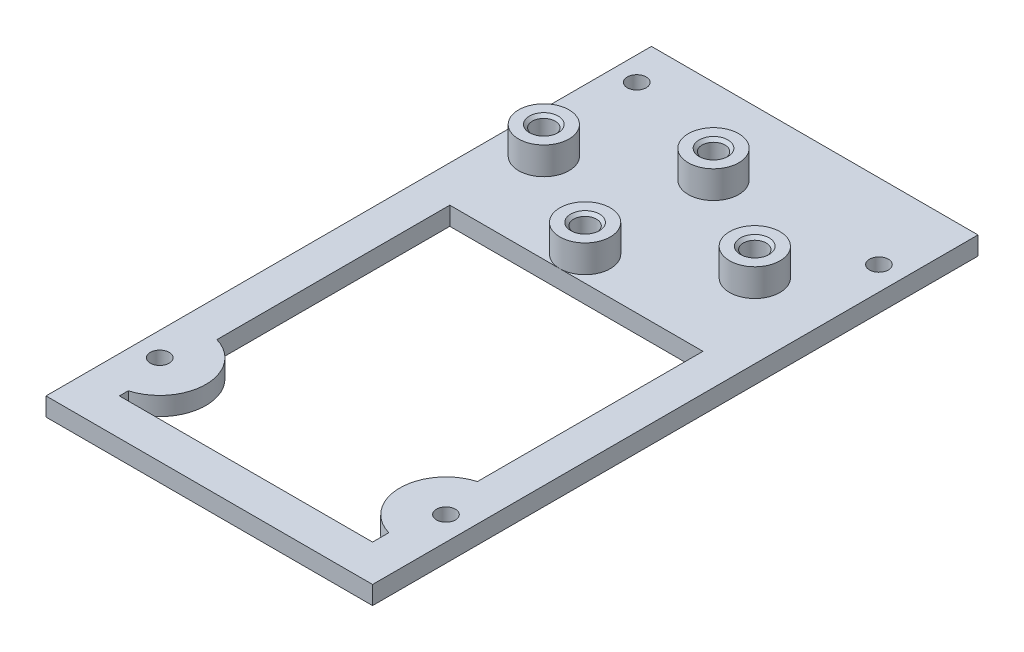
SolidWorks part; units mm, degrees
material "ABS"
ref_plane "Front Plane" through (0, 0, 0) normal (0, 0, 1) x (1, 0, 0)
ref_plane "Top Plane" through (0, 0, 0) normal (0, 1, 0) x (1, 0, 0)
ref_plane "Right Plane" through (0, 0, 0) normal (1, 0, 0) x (0, 0, -1)
sketch "Sketch1" plane through (0, 0, 0) normal (0, 1, 0) x (1, 0, 0)
  line L1 (-26.67, -50.8) -> (26.67, -50.8)
  line L2 (-26.67, -50.8) -> (-26.67, 50.8)
  line L3 (-26.67, 50.8) -> (26.67, 50.8)
  line L4 (26.67, -50.8) -> (26.67, 50.8)
  line L5 (-26.67, -50.8) -> (26.67, 50.8) construction
  line L6 (-26.67, 50.8) -> (26.67, -50.8) construction
  point P1 (0, 0)
  dimension "D1" = 53.34
  dimension "D2" = 101.6
extrude "PCB Plate" add sketch "Sketch1" along normal blind 3.175
hole_wizard "#4 Clearance Hole1" positions "Sketch3" profile "Sketch2" hole size "#4" standard "ANSI Inch" end condition up to next
sketch "Sketch3" plane through (0, 3.175, 0) normal (0, 1, 0) x (1, 0, 0)
  line L0 (-26.67, 50.8) -> (-26.67, -50.8) construction
  line L1 (-26.67, -50.8) -> (26.67, -50.8) construction
  point P0 (-24.13, -36.83)
  point P4 (-24.13, 45.72)
  point P6 (24.13, -35.56)
  point P8 (24.13, 39.37)
  dimension "D1" = 2.54
  dimension "D2" = 13.97
  dimension "D4" = 96.52
  dimension "D6" = 50.8
  dimension "D7" = 15.24
  dimension "D8" = 90.17
sketch "Sketch2" plane through (-24.13, 3.175, 36.83) normal (1, 0, 0) x (0, 0, 1)
  line L0 (0, 0) -> (0, 3.175)
  line L1 (0, 3.175) -> (1.6319, 3.175)
  line L2 (1.6319, 3.175) -> (1.6319, 0)
  line L5 (1.6319, 0) -> (0, 0)
  line L11 (0, -6.35) -> (0, 107.95) construction
  dimension "Thru Hole Dia." = 3.2639
  dimension "Thru Hole Depth" = 3.175
sketch "Sketch5" plane through (0, 0, 0) normal (0, 1, 0) x (1, 0, 0)
  line L8 (28.2575, -52.3875) -> (28.2575, 52.3875)
  line L9 (28.2575, 52.3875) -> (-28.2575, 52.3875)
  line L10 (-28.2575, 52.3875) -> (-28.2575, -52.3875)
  line L11 (-28.2575, -52.3875) -> (28.2575, -52.3875)
  line L12 (28.2575, -52.3875) -> (28.2575, 52.3875)
  line L13 (28.2575, 52.3875) -> (-28.2575, 52.3875)
  line L14 (-28.2575, 52.3875) -> (-28.2575, -52.3875)
  line L15 (-28.2575, -52.3875) -> (28.2575, -52.3875)
  line L20 (26.67, -50.8) -> (26.67, 50.8)
  line L21 (26.67, 50.8) -> (-26.67, 50.8)
  line L22 (-26.67, 50.8) -> (-26.67, -50.8)
  line L23 (-26.67, -50.8) -> (26.67, -50.8)
  line L24 (26.67, -50.8) -> (26.67, 50.8)
  line L25 (26.67, 50.8) -> (-26.67, 50.8)
  line L26 (-26.67, 50.8) -> (-26.67, -50.8)
  line L27 (-26.67, -50.8) -> (26.67, -50.8)
  dimension "D1" = 1.5875
  dimension "D2" = 0
extrude "Border Material" add sketch "Sketch5" along normal up to surface (3.175 mm away) up to face at (-24.13, 3.175, 38.4619)
sketch "Sketch9" plane through (0, 3.175, 0) normal (0, 1, 0) x (1, 0, 0)
  line L0 (-28.2575, 52.3875) -> (28.2575, 52.3875) construction
  line L1 (-21.1138, 37.7317) -> (15.3987, 37.7317) construction
  line L2 (-21.1138, 37.7317) -> (-21.1138, 15.5067) construction
  line L3 (-21.1138, 15.5067) -> (15.3987, 15.5067) construction
  line L4 (15.3987, 37.7317) -> (15.3987, 15.5067) construction
  line L5 (-21.1138, 37.7317) -> (15.3987, 15.5067) construction
  line L6 (-21.1138, 15.5067) -> (15.3987, 37.7317) construction
  line L8 (-28.2575, -52.3875) -> (-28.2575, 52.3875) construction
  circle A0 centre (-2.8575, 37.7317) radius 4.3656
  circle A1 centre (-21.1138, 26.6192) radius 4.3656
  circle A2 centre (-2.8575, 15.5067) radius 4.3656
  circle A3 centre (15.3987, 26.6192) radius 4.3656
  point P4 (-2.8575, 26.6192)
  dimension "D5" = 8.7312
  dimension "D1" = 36.5125
  dimension "D2" = 22.225
  dimension "D3" = 25.4
  dimension "D4" = 25.7683
extrude "Boss-Extrude3" add sketch "Sketch9" along normal blind 4.7625
hole_wizard "CBORE for #4 Socket Head Cap Screw3" positions "Sketch13" profile "Sketch12" counterbore size "#4" standard "ANSI Inch" end condition through all
sketch "Sketch13" plane through (0, 7.9375, 0) normal (0, 1, 0) x (1, 0, 0)
  point P0 (-2.8575, 37.7317)
  point P3 (-21.1138, 26.6192)
  point P6 (-2.8575, 15.5067)
  point P9 (15.3987, 26.6192)
sketch "Sketch12" plane through (-2.8575, 7.9375, -37.7317) normal (1, 0, 0) x (0, 0, 1)
  line L0 (0, 0) -> (0, 7.9375)
  line L1 (0, 7.9375) -> (1.6319, 7.9375)
  line L3 (1.6319, 7.9375) -> (1.632, 4.7625)
  line L4 (1.632, 4.7625) -> (1.9844, 4.7625)
  line L5 (1.9844, 4.7625) -> (1.9844, 0)
  line L7 (1.9844, 0) -> (0, 0)
  line L11 (0, -6.35) -> (0, 107.95) construction
  dimension "Thru Hole Dia." = 3.2639
  dimension "Thru Hole Depth" = 7.9375
  dimension "C'Bore Dia." = 3.9688
  dimension "C'Bore Depth" = 4.7625
sketch "Sketch8" plane through (0, 3.175, 0) normal (0, 1, 0) x (1, 0, 0)
  line L0 (-21.9075, 11.1411) -> (21.9075, 11.1411)
  line L10 (21.9075, 11.1411) -> (21.9075, -27.8937)
  line L11 (-21.9075, -29.1637) -> (-21.9075, 11.1411)
  line L12 (21.9075, -46.0375) -> (21.9075, 46.0375)
  line L13 (21.9075, 46.0375) -> (-21.9075, 46.0375)
  line L14 (-21.9075, 46.0375) -> (-21.9075, -46.0375)
  line L15 (-21.9075, -46.0375) -> (21.9075, -46.0375)
  line L16 (21.9075, -46.0375) -> (21.9075, 46.0375) construction
  line L17 (21.9075, 46.0375) -> (-21.9075, 46.0375) construction
  line L18 (-21.9075, 46.0375) -> (-21.9075, -46.0375) construction
  line L19 (-21.9075, -46.0375) -> (21.9075, -46.0375) construction
  line L20 (21.9075, -43.2263) -> (21.9075, -46.0375)
  line L21 (21.9075, -46.0375) -> (-21.9075, -46.0375)
  line L22 (-21.9075, -46.0375) -> (-21.9075, -44.4963)
  arc A0 (-21.9075, -29.1637) -> (-21.9075, -44.4963) centre (-24.13, -36.83) cw
  circle A1 centre (-2.8575, 15.5067) radius 4.3656 construction
  circle A23 centre (-24.13, -36.83) radius 7.9819
  circle A24 centre (-24.13, -36.83) radius 7.9819 construction
  circle A26 centre (24.13, -35.56) radius 7.9819
  circle A27 centre (24.13, -35.56) radius 7.9819 construction
  arc A29 (21.9075, -27.8937) -> (21.9075, -43.2263) centre (24.13, -35.56) ccw
  dimension "D2" = 6.35
  dimension "D3" = 6.35
  dimension "D4" = 6.35
extrude "Material Reduction Cut" cut sketch "Sketch8" against normal up to next
chamfer "Chamfer2" distance 0.508 angle 45 4 edges at (15.3987, 7.9375, -24.6348) (-2.8575, 7.9375, -13.5223) (-2.8575, 7.9375, -35.7473) (-21.1138, 7.9375, -24.6348)
